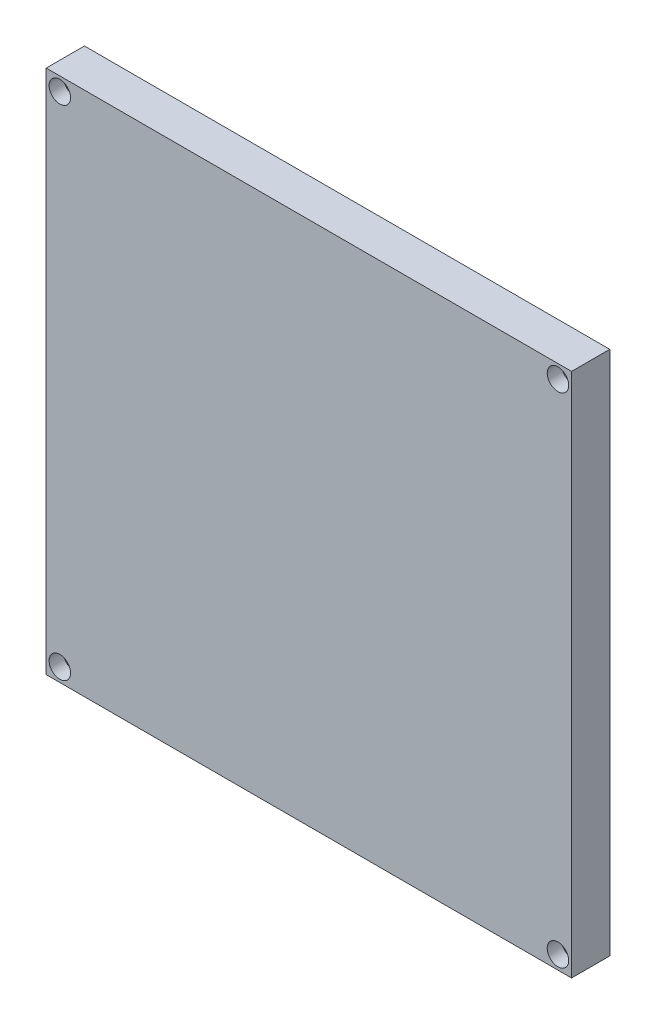
SolidWorks part; units mm, degrees
ref_plane "Front Plane" through (0, 0, 0) normal (0, 0, 1) x (1, 0, 0)
ref_plane "Top Plane" through (0, 0, 0) normal (0, 1, 0) x (1, 0, 0)
ref_plane "Right Plane" through (0, 0, 0) normal (1, 0, 0) x (0, 0, -1)
sketch "Sketch2" plane through (0, 0, 0) normal (0, 0, 1) x (1, 0, 0)
  line L1 (55, -55) -> (-55, -55)
  line L2 (55, -55) -> (55, 55)
  line L3 (55, 55) -> (-55, 55)
  line L4 (-55, -55) -> (-55, 55)
  line L5 (55, -55) -> (-55, 55) construction
  line L6 (55, 55) -> (-55, -55) construction
  point P0 (0, 0)
  dimension "D1" = 110
  dimension "D2" = 110
extrude "Boss-Extrude1" add sketch "Sketch2" along normal blind 8
sketch "Sketch4" plane through (0, 0, 8) normal (0, 0, 1) x (1, 0, 0)
  line L0 (-55, 55) -> (0, 0) construction
  line L1 (5.5, 0) -> (-5.5, 0) construction
  line L2 (0, -5.5) -> (0, 5.5) construction
  circle A0 centre (-52.1491, 52.1491) radius 1.575
  circle A1 centre (-52.1491, -52.1491) radius 1.575
  circle A2 centre (52.1491, -52.1491) radius 1.575
  circle A3 centre (52.1491, 52.1491) radius 1.575
  dimension "D2" = 3.15
  dimension "D1" = 73.75
extrude "Cut-Extrude1" cut sketch "Sketch4" against normal up to next
sketch "Sketch5" plane through (0, 0, 8) normal (0, 0, 1) x (1, 0, 0)
  line L0 (5.5, 0) -> (-5.5, 0) construction
  line L1 (0, -5.5) -> (0, 5.5) construction
  circle A0 centre (-52.1491, 52.1491) radius 2.25
  circle A1 centre (-52.1491, -52.1491) radius 2.25
  circle A2 centre (52.1491, -52.1491) radius 2.25
  circle A3 centre (52.1491, 52.1491) radius 2.25
  dimension "D1" = 4.5
extrude "Cut-Extrude2" cut sketch "Sketch5" against normal blind 3
